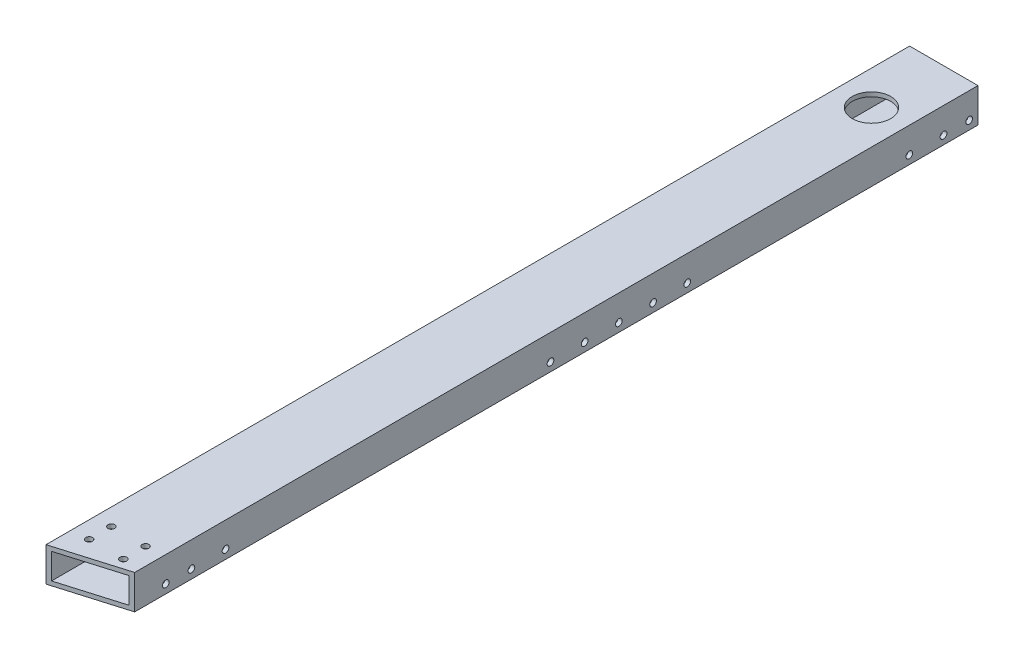
SolidWorks part; units mm, degrees
ref_plane "Front Plane" through (0, 0, 0) normal (0, 0, 1) x (1, 0, 0)
ref_plane "Top Plane" through (0, 0, 0) normal (0, 1, 0) x (1, 0, 0)
ref_plane "Right Plane" through (0, 0, 0) normal (1, 0, 0) x (0, 0, -1)
sketch "Sketch1" plane through (0, 0, 0) normal (0, 0, 1) x (1, 0, 0)
  line L0 (-22.225, 9.525) -> (22.225, 9.525)
  line L2 (-25.4, 12.7) -> (25.4, 12.7)
  line L3 (-25.4, 12.7) -> (-25.4, -12.7)
  line L4 (-25.4, -12.7) -> (25.4, -12.7)
  line L5 (25.4, 12.7) -> (25.4, -12.7)
  line L10 (22.225, 9.525) -> (22.225, -9.525)
  line L11 (-22.225, -9.525) -> (22.225, -9.525)
  line L12 (-22.225, 9.525) -> (-22.225, -9.525)
  point P12 (0, 12.7)
  point P14 (25.4, 0)
  dimension "Wall Thickness" = 3.175
  dimension "Outside Width" = 50.8
  dimension "Outside Height" = 25.4
  dimension "Inside Height" = 19.05
  dimension "Inside Width" = 44.45
sketch "Sketch2" plane through (0, 0, 0) normal (1, 0, 0) x (0, 0, -1)
  line L0 (320.675, 0) -> (-320.675, 0)
  point P4 (0, 0)
  point P7 (-320.675, 0)
  point P10 (320.675, 0)
  dimension "Length" = 641.35
sketch "Sketch3" plane through (0, 0, 0) normal (0, 0, 1) x (1, 0, 0)
  line L21 (25.4, 12.7) -> (-25.4, 12.7)
  line L22 (25.4, -12.7) -> (25.4, 12.7)
  line L23 (-25.4, -12.7) -> (25.4, -12.7)
  line L24 (-25.4, 12.7) -> (-25.4, -12.7)
  line L25 (25.4, 12.7) -> (-25.4, 12.7)
  line L26 (25.4, -12.7) -> (25.4, 12.7)
  line L27 (-25.4, -12.7) -> (25.4, -12.7)
  line L28 (-25.4, 12.7) -> (-25.4, -12.7)
  line L29 (22.225, 9.525) -> (-22.225, 9.525)
  line L30 (22.225, -9.525) -> (22.225, 9.525)
  line L31 (-22.225, -9.525) -> (22.225, -9.525)
  line L32 (-22.225, 9.525) -> (-22.225, -9.525)
  line L33 (22.225, 9.525) -> (-22.225, 9.525)
  line L34 (22.225, -9.525) -> (22.225, 9.525)
  line L35 (-22.225, -9.525) -> (22.225, -9.525)
  line L36 (-22.225, 9.525) -> (-22.225, -9.525)
  dimension "D1" = 0
  dimension "D2" = 0
extrude "Boss-Extrude1" add sketch "Sketch3" along normal up to vertex (320.675 mm away) and the other way up to vertex (320.675 mm away) up to point (0, 0, 320.675) other way up to point (0, 0, -320.675)
sketch "Drawing Reference" plane through (0, 0, 0) normal (1, 0, 0) x (0, 0, -1)
  line L0 (-320.675, 0) -> (320.675, 0) construction
  line L1 (0, -12.7) -> (0, 12.7) construction
  line L2 (-320.675, -12.7) -> (320.675, -12.7) construction
  line L5 (-320.675, 12.7) -> (320.675, 12.7) construction
  point P7 (-284.099, 0)
  point P8 (284.099, 0)
  dimension "D1" = 36.576
sketch "Sketch4" plane through (0, 12.7, 0) normal (0, 1, 0) x (1, 0, 0)
  line L0 (-25.4, -320.675) -> (25.4, -305.6274)
  line L1 (25.4, -320.675) -> (25.4, 320.675) construction
  line L2 (25.4, -320.675) -> (-25.4, -320.675)
  dimension "D1" = 16.5
extrude "Cut-Extrude1" cut sketch "Sketch4" against normal through all and the other way through all flip side to cut
sketch "Sketch8" plane through (0, 12.7, 0) normal (0, 1, 0) x (1, 0, 0)
  line L0 (0, 320.675) -> (0, 266.954) construction
  line L1 (25.4, 320.675) -> (-25.4, 320.675) construction
  circle A0 centre (0, 266.954) radius 14.2875
  dimension "D1" = 53.721
extrude "Cut-Extrude2" cut sketch "Sketch8" against normal through all
sketch "Sketch9" plane through (0, 12.7, 0) normal (0, 1, 0) x (1, 0, 0)
  line L0 (-12.7762, -284.753) -> (12.6238, -284.753) construction
  line L1 (12.6238, -284.753) -> (12.6238, -301.263) construction
  line L2 (12.6238, -301.263) -> (-12.7762, -301.263) construction
  line L3 (-12.7762, -301.263) -> (-12.7762, -284.753) construction
hole_wizard "#10 Clearance Hole1" positions "Sketch10" profile "Sketch11" hole size "#10" standard "ANSI Inch"
sketch "Sketch10" plane through (0, 12.7, 0) normal (0, 1, 0) x (1, 0, 0)
  point P0 (-12.7762, -284.753)
  point P3 (12.6238, -284.753)
  point P6 (12.6238, -301.263)
  point P9 (-12.7762, -301.263)
sketch "Sketch11" plane through (-12.7762, 12.7, 284.753) normal (1, 0, 0) x (0, 0, 1)
  line L0 (0, 0) -> (0, 6.5757)
  line L1 (0, 6.5757) -> (2.4892, 5.08)
  line L2 (2.4892, 5.08) -> (2.4892, 0)
  line L5 (2.4892, 0) -> (0, 0)
  line L10 (0, 6.5757) -> (-2.4892, 5.08) construction
  line L11 (0, -6.35) -> (0, 107.95) construction
  dimension "Hole Dia." = 4.9784
  dimension "Hole Depth" = 5.08
  dimension "Drill Angle" = 118
hole_wizard "#10 Clearance Hole2" positions "Sketch12" profile "Sketch13" hole size "#10" standard "ANSI Inch" end condition through all
sketch "Sketch12" plane through (25.4, 0, 0) normal (1, 0, 0) x (0, 0, -1)
  point P0 (-282.5368, -6.1483)
  point P3 (-263.4868, -6.1483)
  point P6 (-238.125, -6.1483)
  point P9 (3.175, -6.35)
  point P12 (28.575, -6.35)
  point P15 (53.975, -6.35)
  point P18 (79.375, -6.35)
  point P21 (104.775, -6.35)
sketch "Sketch13" plane through (25.4, -6.1483, 282.5368) normal (0, 1, 0) x (0, 0, -1)
  line L0 (0, 0) -> (0, 50.8)
  line L1 (0, 50.8) -> (2.4892, 50.8)
  line L2 (2.4892, 50.8) -> (2.4892, 0)
  line L5 (2.4892, 0) -> (0, 0)
  line L11 (0, -6.35) -> (0, 107.95) construction
  dimension "Thru Hole Dia." = 4.9784
  dimension "Thru Hole Depth" = 50.8
hole_wizard "#10 Clearance Hole3" positions "Sketch14" profile "Sketch15" hole size "#10" standard "ANSI Inch"
sketch "Sketch14" plane through (25.4, 0, 0) normal (1, 0, 0) x (0, 0, -1)
  point P0 (269.6733, -6.3882)
  point P3 (295.0733, -6.3882)
  point P6 (314.1233, -6.3882)
sketch "Sketch15" plane through (25.4, -6.3882, -269.6733) normal (0, 1, 0) x (0, 0, -1)
  line L0 (0, 0) -> (0, 4.7977)
  line L1 (0, 4.7977) -> (2.4892, 3.302)
  line L2 (2.4892, 3.302) -> (2.4892, 0)
  line L5 (2.4892, 0) -> (0, 0)
  line L10 (0, 4.7977) -> (-2.4892, 3.302) construction
  line L11 (0, -6.35) -> (0, 107.95) construction
  dimension "Hole Dia." = 4.9784
  dimension "Hole Depth" = 3.302
  dimension "Drill Angle" = 118
equation "\"D1@Drawing Reference\"=\"Outside Width@Sketch1\" * 0.72"
